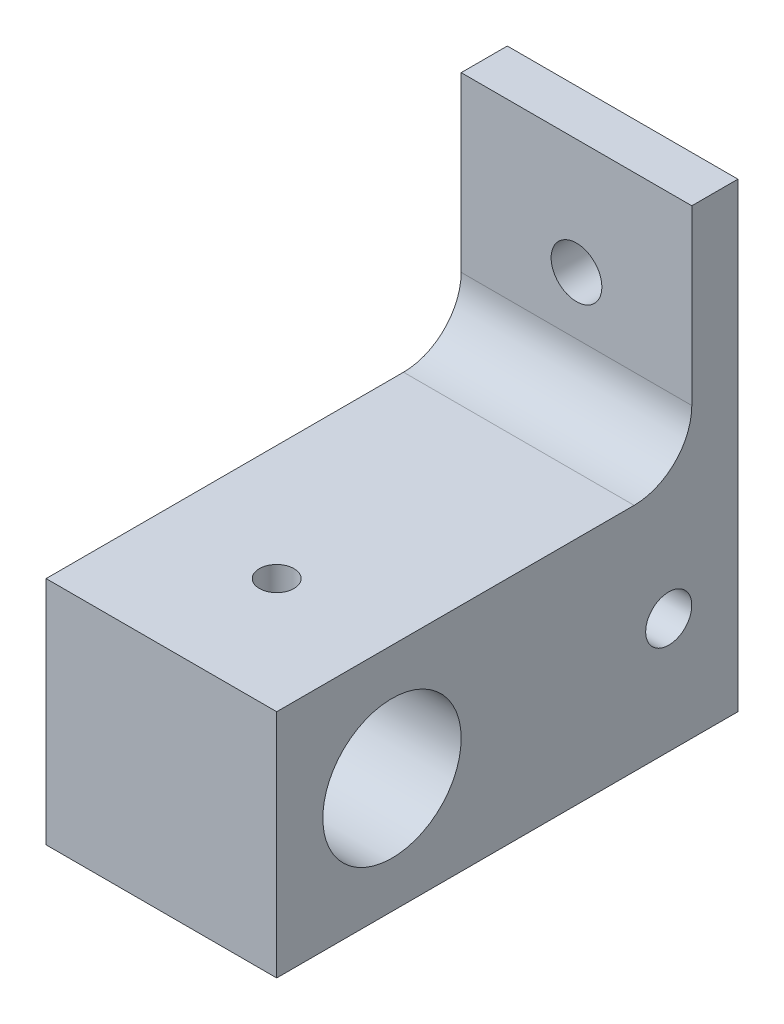
SolidWorks part; units mm, degrees
ref_plane "Płaszczyzna przednia" through (0, 0, 0) normal (0, 0, 1) x (1, 0, 0)
ref_plane "Płaszczyzna górna" through (0, 0, 0) normal (0, 1, 0) x (1, 0, 0)
ref_plane "Płaszczyzna prawa" through (0, 0, 0) normal (1, 0, 0) x (0, 0, -1)
sketch "Sketch1" plane through (0, 0, 0) normal (0, 0, 1) x (1, 0, 0)
  line L1 (0, 0) -> (20, 0)
  line L2 (0, 0) -> (0, 20)
  line L3 (0, 20) -> (20, 20)
  line L4 (20, 0) -> (20, 20)
  line L5 (0, 0) -> (20, 20) construction
  line L6 (0, 20) -> (20, 0) construction
  point P4 (10, 10)
  dimension "D1" = 20
  dimension "D2" = 20
extrude "Boss-Extrude1" add sketch "Sketch1" along normal blind 40
sketch "Sketch2" plane through (20, 0, 0) normal (1, 0, 0) x (0, 0, -1)
  line L0 (-40, 0) -> (-40, 20) construction
  line L1 (-40, 0) -> (0, 0) construction
  circle A0 centre (-30, 10) radius 6
  dimension "D1" = 12
  dimension "D2" = 10
  dimension "D3" = 10
extrude "Cut-Extrude1" cut sketch "Sketch2" against normal blind 30
hole_wizard "Ø3.0mm Dowel Hole1" positions "Sketch3" profile "Sketch4" hole size "Ø3.0" standard "ANSI Metric"
sketch "Sketch3" plane through (0, 20, 0) normal (0, 1, 0) x (1, 0, 0)
  line L0 (20, -40) -> (20, 0) construction
  line L2 (20, -40) -> (0, -40) construction
  point P0 (10, -30)
  dimension "D1" = 10
  dimension "D2" = 10
sketch "Sketch4" plane through (10, 20, 30) normal (1, 0, 0) x (0, 0, 1)
  line L0 (0, 0) -> (0, 4)
  line L1 (0, 4) -> (1.5, 4)
  line L2 (1.5, 4) -> (1.5, 0)
  line L5 (1.5, 0) -> (0, 0)
  line L11 (0, -6.35) -> (0, 107.95) construction
  dimension "Thru Hole Dia." = 3
  dimension "Thru Hole Depth" = 4
sketch "Sketch5" plane through (0, 0, 0) normal (-1, 0, 0) x (0, 0, 1)
  line L0 (0, 20) -> (0, 0) construction
  line L1 (40, 0) -> (0, 0) construction
  circle A0 centre (6, 10) radius 2
  dimension "D1" = 4
  dimension "D2" = 6
  dimension "D3" = 10
extrude "Cut-Extrude2" cut sketch "Sketch5" against normal blind 30
sketch "Sketch6" plane through (0, 20, 0) normal (0, 1, 0) x (1, 0, 0)
  line L0 (0, -40) -> (0, 0) construction
  line L1 (20, 0) -> (0, 0)
  line L2 (20, 0) -> (20, -4)
  line L3 (20, -4) -> (0, -4)
  line L4 (0, 0) -> (0, -4)
  line L5 (20, 0) -> (0, -4) construction
  line L6 (20, -4) -> (0, 0) construction
  point P4 (10, -2)
  dimension "D1" = 4
extrude "Boss-Extrude2" add sketch "Sketch6" along normal blind 20
hole_wizard "Ø4.4 (4.4) Diameter Hole1" positions "Sketch7" profile "Sketch8" hole size "Ø4.4" standard "ANSI Metric" end condition up to next
sketch "Sketch7" plane through (0, 0, 4) normal (0, 0, 1) x (1, 0, 0)
  line L0 (0, 40) -> (20, 40) construction
  line L1 (0, 40) -> (0, 20) construction
  point P0 (10, 30)
  dimension "D1" = 10
  dimension "D2" = 10
sketch "Sketch8" plane through (10, 30, 4) normal (1, 0, 0) x (0, -1, 0)
  line L0 (0, 0) -> (0, 4)
  line L1 (0, 4) -> (2.2, 4)
  line L2 (2.2, 4) -> (2.2, 0)
  line L5 (2.2, 0) -> (0, 0)
  line L11 (0, -6.35) -> (0, 107.95) construction
  dimension "Thru Hole Dia." = 4.4
  dimension "Thru Hole Depth" = 4
fillet "Fillet1" radius 5 1 edges at (10, 20, 4)
